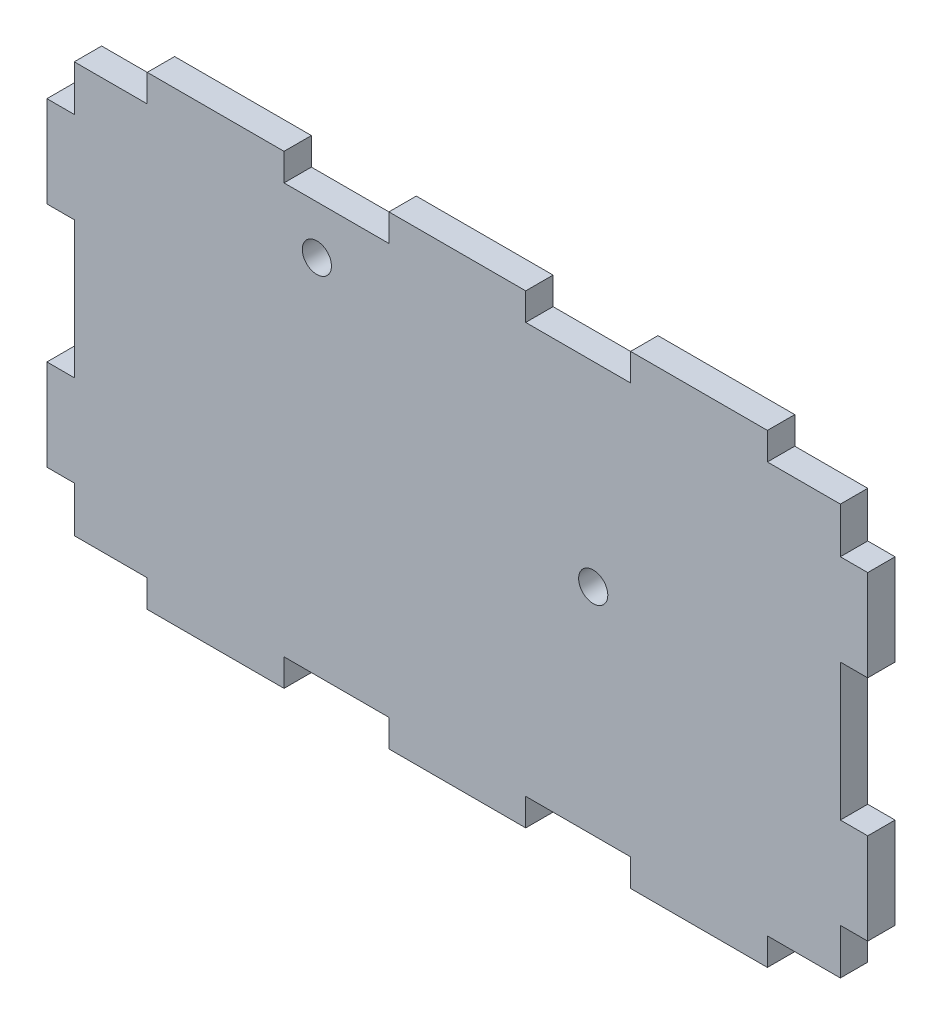
SolidWorks part; units mm, degrees
ref_plane "前视基准面" through (0, 0, 0) normal (0, 0, 1) x (1, 0, 0)
ref_plane "上视基准面" through (0, 0, 0) normal (0, 1, 0) x (1, 0, 0)
ref_plane "右视基准面" through (0, 0, 0) normal (1, 0, 0) x (0, 0, -1)
sketch "草图1" plane through (0, 0, 0) normal (0, 0, 1) x (1, 0, 0)
  line L0 (-42, 0) -> (42, 0) construction
  line L1 (-42, -22.5) -> (-34, -22.5)
  line L2 (-42, -22.5) -> (-42, -17.5)
  line L3 (-42, 22.5) -> (-34, 22.5)
  line L4 (42, -22.5) -> (42, -17.5)
  line L5 (-42, -22.5) -> (42, 22.5) construction
  line L6 (-42, 22.5) -> (42, -22.5) construction
  line L7 (7.5, 22.5) -> (19, 22.5)
  line L8 (-34, 22.5) -> (-34, 25.5)
  line L9 (-34, 25.5) -> (-19, 25.5)
  line L10 (-19, 22.5) -> (-19, 25.5)
  line L11 (34, 22.5) -> (42, 22.5)
  line L12 (-7.5, 22.5) -> (-7.5, 25.5)
  line L13 (-7.5, 25.5) -> (7.5, 25.5)
  line L14 (7.5, 22.5) -> (7.5, 25.5)
  line L15 (0, -22.5) -> (0, 22.5) construction
  line L16 (19, 22.5) -> (19, 25.5)
  line L17 (34, 25.5) -> (19, 25.5)
  line L18 (34, 22.5) -> (34, 25.5)
  line L19 (-19, 22.5) -> (-7.5, 22.5)
  line L20 (34, -22.5) -> (34, -25.5)
  line L21 (34, -25.5) -> (19, -25.5)
  line L22 (19, -22.5) -> (19, -25.5)
  line L23 (7.5, -22.5) -> (7.5, -25.5)
  line L24 (-7.5, -25.5) -> (7.5, -25.5)
  line L25 (-7.5, -22.5) -> (-7.5, -25.5)
  line L26 (-19, -22.5) -> (-19, -25.5)
  line L27 (-34, -22.5) -> (-34, -25.5)
  line L28 (-34, -25.5) -> (-19, -25.5)
  line L29 (-19, -22.5) -> (-7.5, -22.5)
  line L30 (7.5, -22.5) -> (19, -22.5)
  line L31 (34, -22.5) -> (42, -22.5)
  line L32 (-42, -7.5) -> (-45, -7.5)
  line L33 (-42, 17.5) -> (-45, 17.5)
  line L34 (-42, -7.5) -> (-42, 7.5)
  line L35 (-42, 7.5) -> (-45, 7.5)
  line L36 (-45, 17.5) -> (-45, 7.5)
  line L37 (-45, -17.5) -> (-45, -7.5)
  line L38 (-42, -17.5) -> (-45, -17.5)
  line L39 (-42, 17.5) -> (-42, 22.5)
  line L40 (42, -17.5) -> (45, -17.5)
  line L41 (45, -17.5) -> (45, -7.5)
  line L42 (42, -7.5) -> (45, -7.5)
  line L43 (42, 7.5) -> (45, 7.5)
  line L44 (45, 17.5) -> (45, 7.5)
  line L45 (42, 17.5) -> (45, 17.5)
  line L46 (42, 17.5) -> (42, 22.5)
  line L47 (42, -7.5) -> (42, 7.5)
  point P0 (0, 0)
  point P14 (0, 25.5)
  point P17 (0, 0)
  point P20 (0, 0)
  dimension "D1" = 45
  dimension "D2" = 84
  dimension "D3" = 3
  dimension "D4" = 15
  dimension "D5" = 3
  dimension "D6" = 15
  dimension "D7" = 8
  dimension "D8" = 3
  dimension "D9" = 10
  dimension "D10" = 5
extrude "凸台-拉伸1" add sketch "草图1" along normal blind 3
sketch "草图3" plane through (0, 0, 3) normal (0, 0, 1) x (1, 0, 0)
  circle A0 centre (-15.4, 17.2) radius 1.6
  circle A1 centre (14.9, 1.1) radius 1.6
  dimension "D1" = 3.2
  dimension "D2" = 3.2
extrude "切除-拉伸1" cut sketch "草图3" against normal through all
